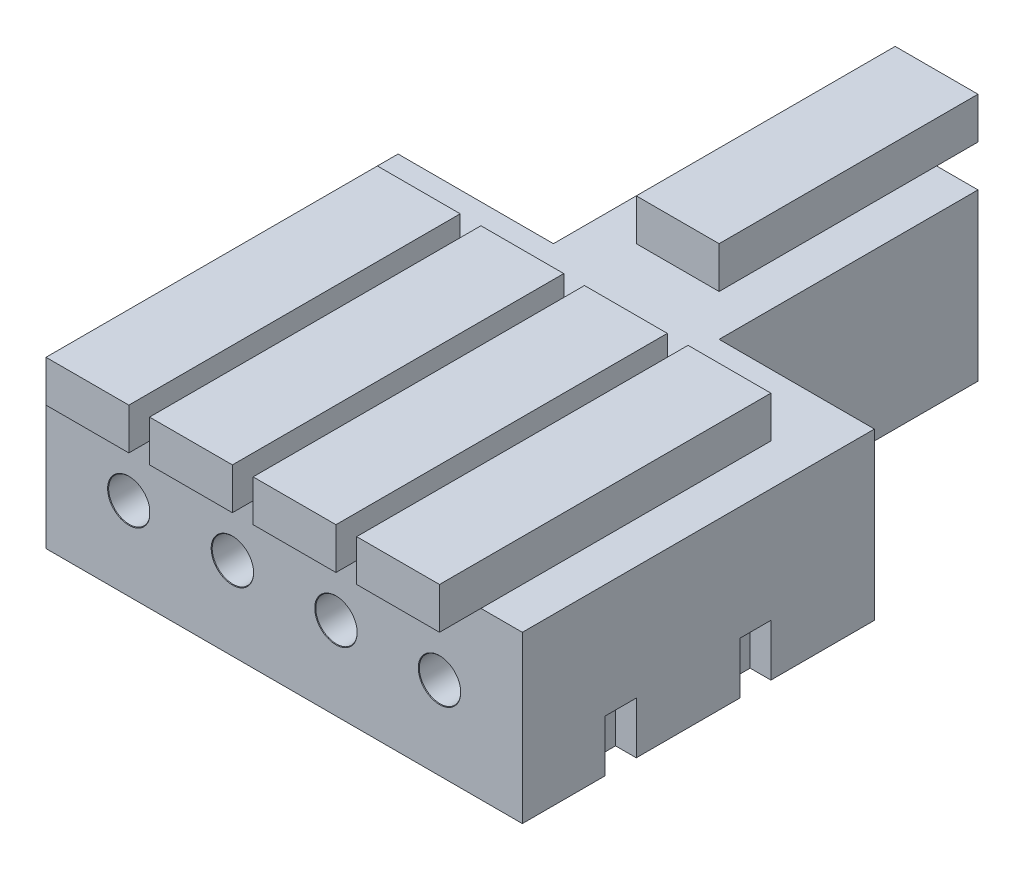
SolidWorks part; units mm, degrees
material "ABS"
ref_plane "Front Plane" through (0, 0, 0) normal (0, 0, 1) x (1, 0, 0)
ref_plane "Top Plane" through (0, 0, 0) normal (0, 1, 0) x (1, 0, 0)
ref_plane "Right Plane" through (0, 0, 0) normal (1, 0, 0) x (0, 0, -1)
sketch "Sketch1" plane through (0, 0, 0) normal (0, 1, 0) x (1, 0, 0)
  line L1 (0, 0) -> (8, 0)
  line L2 (0, 0) -> (0, 17)
  line L3 (0, 17) -> (8, 17)
  line L4 (8, 0) -> (8, 17)
  dimension "D1" = 8
  dimension "D2" = 17
extrude "connector_body" add sketch "Sketch1" along normal blind 8
sketch "Sketch2" plane through (0, 0, 0) normal (0, 0, -1) x (-1, 0, 0)
  line L0 (0, 8) -> (0, 0) construction
  line L1 (-8, 8) -> (0, 8) construction
  point P0 (-4, 4)
  dimension "D1" = 4
  dimension "D2" = 4
hole_wizard "cable_hole" positions "Sketch2" profile "Sketch3" hole size "Ø2.0" standard "DIN"
sketch "Sketch3" plane through (4, 4, 0) normal (1, 0, 0) x (0, -1, 0)
  line L0 (0, 0) -> (0, 10.6009)
  line L1 (0, 10.6009) -> (1, 10)
  line L2 (1, 10) -> (1, 0.025)
  line L3 (1, 0.025) -> (1.025, 0)
  line L5 (1.025, 0) -> (0, 0)
  line L6 (-1, 0.025) -> (-1.025, 0) construction
  line L10 (0, 10.6009) -> (-1, 10) construction
  line L11 (0, -6.35) -> (0, 107.95) construction
  dimension "Hole Dia." = 2
  dimension "Hole Depth" = 10
  dimension "Near C'Sink Dia." = 2.05
  dimension "Near C'Sink Angle" = 90
  dimension "Drill Angle" = 118
sketch "Sketch4" plane through (0, 8, 0) normal (0, 1, 0) x (1, 0, 0)
  line L0 (8, 0) -> (8, 17) construction
  line L1 (2, 14) -> (6, 14)
  line L2 (2, 14) -> (2, -2)
  line L3 (2, -2) -> (6, -2)
  line L4 (6, 14) -> (6, -2)
  line L6 (8, 17) -> (0, 17) construction
  dimension "D1" = 4
  dimension "D2" = 2
  dimension "D3" = 3
  dimension "D4" = 16
extrude "clamp" add sketch "Sketch4" along normal blind 2
pattern_linear "connector_pattern" count 4 spacing 5 along (1, 0, 0) of "connector_body", "cable_hole", "clamp"
sketch "Sketch5" plane through (0, 8, 0) normal (0, 1, 0) x (1, 0, 0)
  line L0 (23, 17) -> (0, 17) construction
  line L1 (7.5, 17) -> (15.5, 17)
  line L2 (7.5, 17) -> (7.5, 29.5)
  line L3 (7.5, 29.5) -> (15.5, 29.5)
  line L4 (15.5, 17) -> (15.5, 29.5)
  line L5 (0, 17) -> (0, 0) construction
  dimension "D1" = 8
  dimension "D2" = 7.5
  dimension "D3" = 12.5
extrude "single_body" add sketch "Sketch5" against normal up to vertex (8 mm away)
sketch "Sketch6" plane through (0, 0, 0) normal (-1, 0, 0) x (0, 0, 1)
  line L0 (-17, 0) -> (0, 0) construction
  line L1 (-12, 0) -> (-10.5, 0)
  line L2 (-12, 0) -> (-12, 2.5004)
  line L3 (-12, 2.5004) -> (-10.5, 2.5004)
  line L4 (-10.5, 0) -> (-10.5, 2.5004)
  line L5 (-17, 0) -> (-17, 8) construction
  line L6 (-5.5, 0) -> (-4, 0)
  line L7 (-5.5, 0) -> (-5.5, 2.5004)
  line L8 (-5.5, 2.5004) -> (-4, 2.5004)
  line L9 (-4, 0) -> (-4, 2.5004)
  point P12 (-4.75, 0)
  dimension "D1" = 5
  dimension "D2" = 1.5
  dimension "D3" = 1.5
  dimension "D4" = 2.5004
  dimension "D5" = 5
extrude "chaining_nobs" add sketch "Sketch6" along normal blind 1
sketch "Sketch7" plane through (0, 0, 0) normal (0, -1, 0) x (1, 0, 0)
  line L0 (23, 0) -> (23, -17) construction
  line L1 (23, -4) -> (22, -4)
  line L2 (23, -4) -> (23, -5.5)
  line L3 (23, -5.5) -> (22, -5.5)
  line L4 (22, -4) -> (22, -5.5)
  line L5 (-1, -10.5) -> (0, -10.5) construction
  line L6 (22, -12) -> (23, -12)
  line L7 (22, -12) -> (22, -10.5)
  line L8 (22, -10.5) -> (23, -10.5)
  line L9 (23, -12) -> (23, -10.5)
  line L11 (-1, -5.5) -> (0, -5.5) construction
  dimension "D1" = 1
  dimension "D2" = 1.5
sketch "Sketch8" plane through (0, 8, 0) normal (0, 1, 0) x (1, 0, 0)
  line L0 (7.5, 29.5) -> (7.5, 17) construction
  line L1 (9.5, 19) -> (13.5, 19)
  line L2 (9.5, 19) -> (9.5, 31.5)
  line L3 (9.5, 31.5) -> (13.5, 31.5)
  line L4 (13.5, 19) -> (13.5, 31.5)
  line L5 (23, 17) -> (15.5, 17) construction
  line L6 (15.5, 29.5) -> (7.5, 29.5) construction
  dimension "D1" = 4
  dimension "D2" = 2
  dimension "D3" = 2
  dimension "D4" = 2
extrude "chaining_nobs_cutout" cut sketch "Sketch7" against normal up to vertex (2.5004 mm away)
extrude "single_body_clamp" add sketch "Sketch8" along normal up to vertex (2 mm away)
sketch "Sketch9" plane through (0, 0, 0) normal (0, -1, 0) x (1, 0, 0)
  line L1 (7.5, -29.5) -> (7.5, -17) construction
  line L2 (15.5, -29.5) -> (7.5, -29.5) construction
  circle A0 centre (5.5, -19) radius 2.25
  circle A1 centre (5.5, -19) radius 1.5
  circle A2 centre (17.5, -19) radius 1.5
  circle A3 centre (17.5, -19) radius 2.25
  dimension "D2" = 2
  dimension "D3" = 4.5
  dimension "D4" = 3
  dimension "D1" = 12
  dimension "D5" = 10.5
extrude "mounting_rings" add sketch "Sketch9" against normal blind 2
